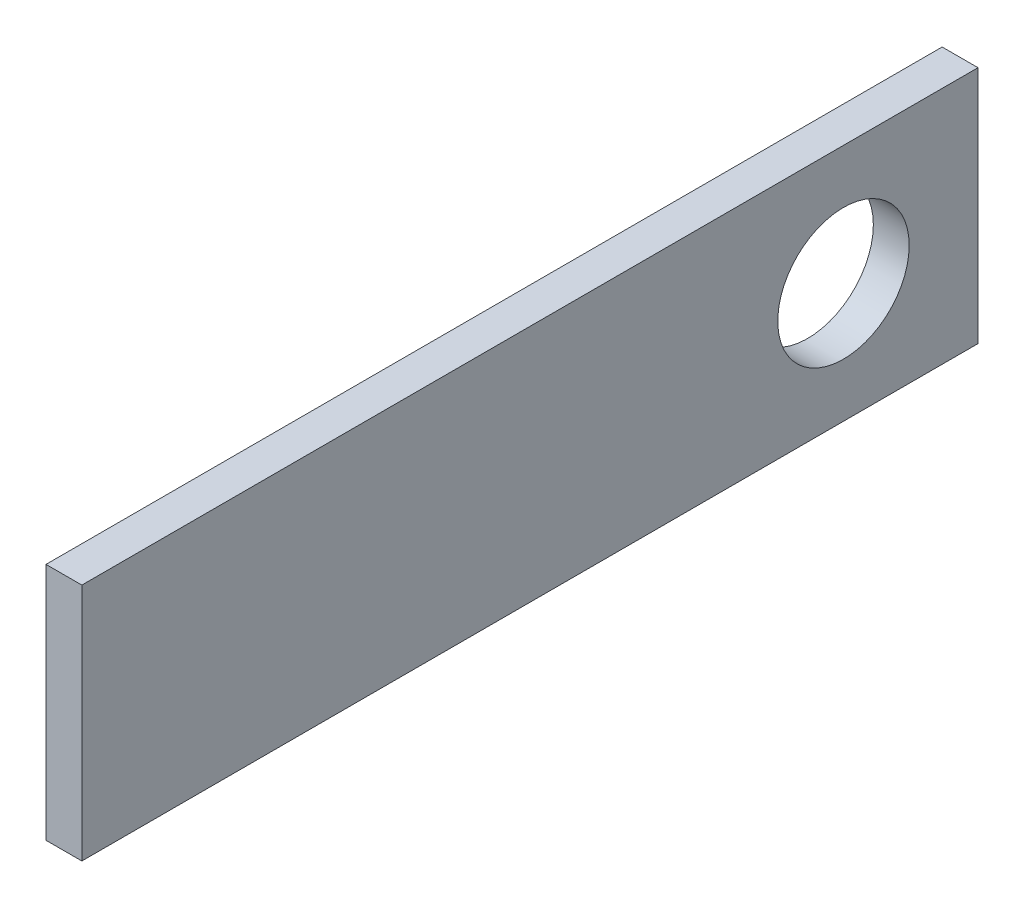
SolidWorks part; units mm, degrees
ref_plane "Front Plane" through (0, 0, 0) normal (0, 0, 1) x (1, 0, 0)
ref_plane "Top Plane" through (0, 0, 0) normal (0, 1, 0) x (1, 0, 0)
ref_plane "Right Plane" through (0, 0, 0) normal (1, 0, 0) x (0, 0, -1)
sketch "Sketch1" plane through (0, 0, 0) normal (1, 0, 0) x (0, 0, -1)
  line L0 (55, 0) -> (-55, 0) construction
  line L1 (-75, 20) -> (75, 20)
  line L2 (-75, 20) -> (-75, -20)
  line L3 (-75, -20) -> (75, -20)
  line L4 (75, 20) -> (75, -20)
  line L5 (-75, 20) -> (75, -20) construction
  line L6 (-75, -20) -> (75, 20) construction
  circle A0 centre (52.4813, 0) radius 11
  point P0 (0, 0)
  dimension "D3" = 22
  dimension "D1" = 150
  dimension "D2" = 40
extrude "Boss-Extrude1" add sketch "Sketch1" along normal mid plane 6
